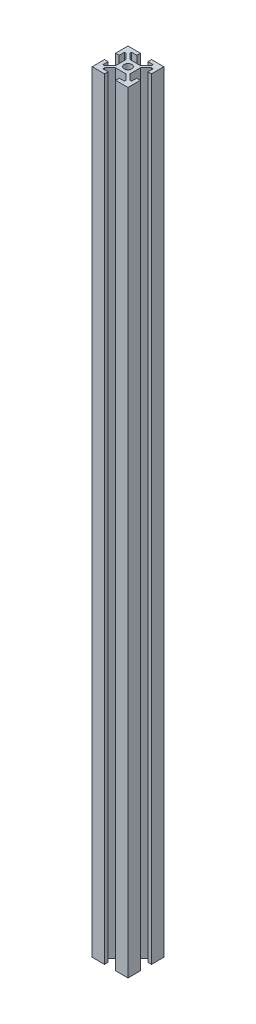
SolidWorks part; units mm, degrees
ref_plane "Front" through (0, 0, 0) normal (0, 0, 1) x (1, 0, 0)
ref_plane "Top" through (0, 0, 0) normal (0, 1, 0) x (1, 0, 0)
ref_plane "Right" through (0, 0, 0) normal (1, 0, 0) x (0, 0, -1)
sketch "스케치1" plane through (0, 0, 0) normal (0, 1, 0) x (1, 0, 0)
  line L0 (3.1, 8) -> (6, 8)
  line L1 (-10.001, 9.999) -> (-3.1, 9.999)
  line L2 (-10.001, 9.999) -> (-10.001, 3.1)
  line L3 (-10.001, -9.999) -> (-3.1, -9.999)
  line L4 (10.001, 9.999) -> (10.001, 3.1)
  line L5 (-10.001, 9.999) -> (-1.5204, 1.5201) construction
  line L6 (-10.001, -9.999) -> (-1.5204, -1.5201) construction
  line L11 (-7, -7) -> (-1.5203, -1.5203) construction
  line L12 (-7, 7) -> (-1.5203, 1.5203) construction
  line L15 (-3.1, 9.999) -> (-3.1, 8)
  line L17 (3.1, 9.999) -> (3.1, 8)
  line L18 (8, -3.1) -> (8, -6)
  line L27 (-3.1, 8) -> (-6, 8)
  line L28 (6, 8) -> (6, 7)
  line L30 (0, 4) -> (3, 4)
  line L31 (3, 4) -> (6, 7)
  line L32 (-6, 8) -> (-6, 7)
  line L33 (-6, 7) -> (-3, 4)
  line L34 (0, 4) -> (-3, 4)
  line L35 (3.1, 9.999) -> (10.001, 9.999)
  line L36 (10.001, 3.1) -> (8, 3.1)
  line L37 (10.001, -3.1) -> (8, -3.1)
  line L38 (8, 3.1) -> (8, 6)
  line L39 (8, -6) -> (7, -6)
  line L40 (4, 0) -> (4, -3)
  line L41 (4, -3) -> (7, -6)
  line L42 (8, 6) -> (7, 6)
  line L43 (7, 6) -> (4, 3)
  line L44 (4, 0) -> (4, 3)
  line L45 (-3.1, -8) -> (-6, -8)
  line L47 (3.1, -9.999) -> (3.1, -8)
  line L48 (-3.1, -9.999) -> (-3.1, -8)
  line L49 (3.1, -8) -> (6, -8)
  line L50 (-6, -8) -> (-6, -7)
  line L51 (0, -4) -> (-3, -4)
  line L52 (-3, -4) -> (-6, -7)
  line L53 (6, -8) -> (6, -7)
  line L54 (6, -7) -> (3, -4)
  line L55 (0, -4) -> (3, -4)
  line L56 (-8, 3.1) -> (-8, 6)
  line L58 (-10.001, -3.1) -> (-8, -3.1)
  line L59 (-10.001, 3.1) -> (-8, 3.1)
  line L60 (-8, -3.1) -> (-8, -6)
  line L61 (-8, 6) -> (-7, 6)
  line L62 (-4, 0) -> (-4, 3)
  line L63 (-4, 3) -> (-7, 6)
  line L64 (-8, -6) -> (-7, -6)
  line L65 (-7, -6) -> (-4, -3)
  line L66 (-4, 0) -> (-4, -3)
  line L67 (-10.001, -3.1) -> (-10.001, -9.999)
  line L69 (3.1, -9.999) -> (10.001, -9.999)
  line L72 (10.001, -3.1) -> (10.001, -9.999)
  line L73 (1.5203, -1.5203) -> (7, -7) construction
  line L74 (1.5204, -1.5201) -> (10.001, -9.999) construction
  line L75 (1.5203, 1.5203) -> (7, 7) construction
  line L76 (1.5204, 1.5201) -> (10.001, 9.999) construction
  circle A4 centre (0, 0) radius 2.15
  point P0 (0, 0)
  point P6 (0, 0)
  point P21 (0, 0)
  point P22 (0, 10)
  point P31 (0, 0)
  point P40 (10, 0)
  point P46 (0, 0)
  point P53 (0, -10)
  point P59 (0, 0)
  point P66 (-10, 0)
  point P72 (0, 0)
  dimension "D1" = 4
extrude "보스-돌출1" add sketch "스케치1" along normal blind 430
sketch "스케치3" plane through (10.001, 0, 0) normal (1, 0, 0) x (0, 0, -1)
  line L0 (0, 0) -> (0, 430) construction
  line L1 (-3, 430) -> (3, 430) construction
  circle A0 centre (0, 215) radius 3
extrude "컷-돌출1" cut sketch "스케치3" against normal blind 26
